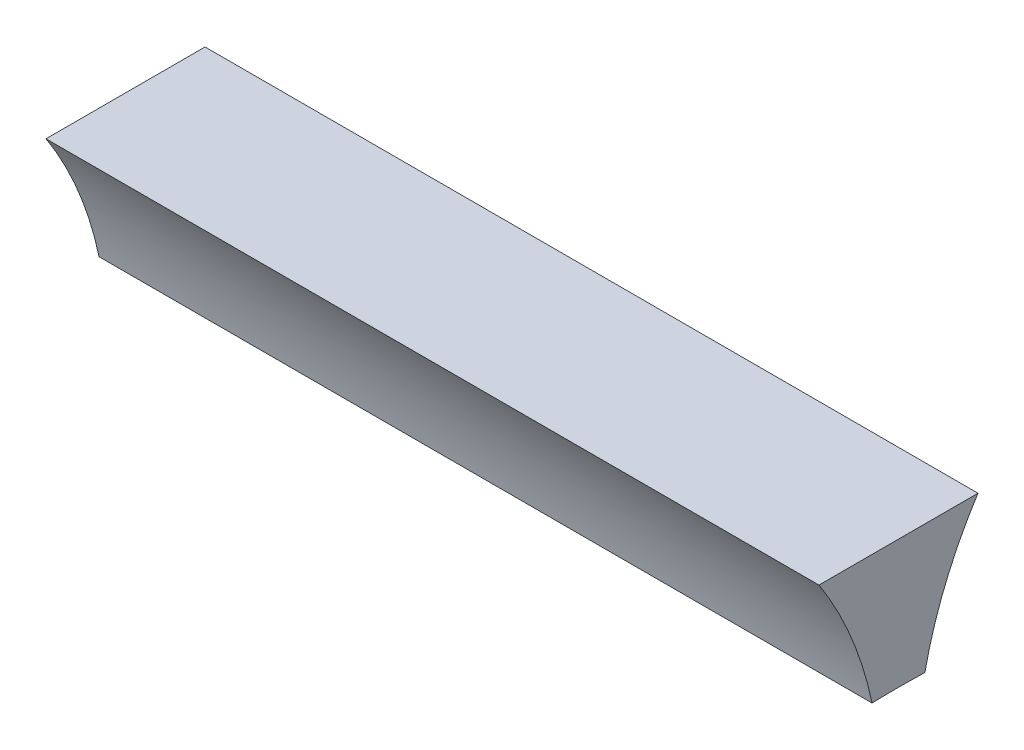
SolidWorks part; units mm, degrees
ref_plane "Plane1" through (0, 0, 0) normal (0, 0, 1) x (1, 0, 0)
ref_plane "Plane2" through (0, 0, 0) normal (0, 1, 0) x (1, 0, 0)
ref_plane "Plane3" through (0, 0, 0) normal (1, 0, 0) x (0, 0, -1)
sketch "HoldingSke" plane through (0, 0, 0) normal (0, 1, 0) x (1, 0, 0)
  line L0 (0, 0) -> (0.5591, -0.3631)
  line L1 (-15, 0) -> (100, 0) construction
  line L2 (0, 0) -> (-2.1039, 2.3779)
  line L3 (0, 0) -> (-11.863, 4.5341)
  line L4 (0, 0) -> (7.2428, 4.7035)
  line L5 (0, 0) -> (-46.8476, -17.4728)
  line L6 (0, 0) -> (-16.5793, -11.1861)
  line L7 (-2.1039, 2.3779) -> (8.6586, 51.2059)
  line L8 (-76.2, 54.61) -> (-72.9, 54.61)
  line L9 (-71.009, 38.7566) -> (-53.1078, 45.2721)
  line L10 (-76.2, 71.12) -> (104.1128, 71.12)
  line L11 (0, 0) -> (-20, 0)
  line L12 (-76.2, 101.6) -> (-76.147, 101.6)
  line L13 (24.9733, 27.94) -> (52.9518, 28.4284)
  line L14 (24.9733, 27.94) -> (24.9743, 27.94)
  line L15 (24.9733, 27.94) -> (100.4006, 29.5858)
  line L16 (-63.627, -1.5) -> (-12.827, -1.5)
  circle A0 centre (0, 0) radius 15
  circle A1 centre (0, 0) radius 22.874
  circle A2 centre (0, 0) radius 37.5
  circle A3 centre (0, 0) radius 15
  dimension "MHD" = 45.748
  dimension "Hub_dia" = 75
  dimension "Bore" = 30
  dimension "MBD" = 30
  dimension "Num_teeth" = 33
  dimension "Pitch" = 0.6667
  dimension "Overall_len" = 50
  dimension "Show_teeth" = 33
  dimension "Thickness" = 20
  dimension "OAL" = 50.0001
  dimension "T_dim" = 3.3
  dimension "Ap" = 20
  dimension "H" = 19.05
  dimension "Pitch_radius" = 180.3128
  dimension "Width" = 20
  dimension "Backlash" = 0.053
  dimension "Addendum_fac" = 1
  dimension "Dedendum_fac" = 1.25
  dimension "Clearance_fac" = 0.25
  dimension "Dedendum_add" = 0.001
  dimension "Module" = 1.5
sketch "BasProSke" plane through (0, 0, 0) normal (0, 1, 0) x (1, 0, 0)
  line L0 (-10, 0) -> (60, 0) construction
  line L1 (0, 0) -> (0, 26.25)
  line L2 (0, 0) -> (20, 0)
  line L3 (20, 0) -> (20, 26.25)
  line L4 (20, 26.25) -> (0, 26.25)
  dimension "Thickness" = 20
  dimension "Diameter" = 52.5
revolve "Base-Revolve" add sketch "BasProSke" angle 360 about L0
sketch "TooCutSke" plane through (0, 0, 0) normal (1, 0, 0) x (0, 0, -1)
  line L1 (0, 0) -> (0, 107) construction
  line L2 (0, 0) -> (-1.2704, 24.7174) construction
  line L3 (0, 0) -> (-4.7008, 49.2285) construction
  line L4 (-1.2704, 24.7174) -> (-2.3504, 24.6142) construction
  arc A0 (0.6837, 22.8638) -> (-0.6837, 22.8638) centre (0, 0) ccw
  arc A1 (2.0575, 26.1947) -> (-2.0575, 26.1947) centre (0, 0) ccw
  circle A2 centre (0, 0) radius 24.75 construction
  circle A3 centre (0, 0) radius 23.2574 construction
  arc A4 (-0.6837, 22.8638) -> (-2.0575, 26.1947) centre (-10.3699, 20.8176) ccw
  arc A5 (2.0575, 26.1947) -> (0.6837, 22.8638) centre (10.3699, 20.8176) ccw
  dimension "Root_dia" = 45.748
  dimension "Overcut_dia" = 52.5508
  dimension "Pitch_dia" = 49.5
  dimension "Base_dia" = 46.5148
  dimension "Flank_rad" = 9.9
  dimension "Half_ang" = 5.455
  dimension "Half_CT" = 1.0849
extrude "ToothCut" cut sketch "TooCutSke" along normal through all
fillet "Breaks" [suppressed] radius 0.03
fillet "RootFillets" [suppressed] radius 0.376
pattern_circular "TeethCuts" count 33 every 10.909 about axis through (-10, 0, 0) along (1, 0, 0) of "ToothCut", "RootFillets", "Breaks"
sketch "HubNeaOneSke" plane through (0, 0, 0) normal (-1, 0, 0) x (0, 0, 1)
  circle A0 centre (0, 0) radius 22.874
  dimension "Diameter" = 45.748
extrude "HubNearOne" [suppressed] add sketch "HubNeaOneSke" along normal blind 30.0001
sketch "HubNeaBotSke" plane through (0, 0, 0) normal (-1, 0, 0) x (0, 0, 1)
  circle A0 centre (0, 0) radius 22.874
  dimension "Diameter" = 45.748
extrude "HubNearBoth" [suppressed] add sketch "HubNeaBotSke" along normal blind 15
ref_plane "FarPln" through (20, 0, 0) normal (1, 0, 0) x (0, 0, -1)
sketch "HubFarSke" plane through (20, 0, 0) normal (1, 0, 0) x (0, 0, -1)
  circle A0 centre (0, 0) radius 22.874
  dimension "Diameter" = 45.748
extrude "HubFar" [suppressed] add sketch "HubFarSke" along normal blind 15
sketch "BorSke" plane through (0, 0, 0) normal (1, 0, 0) x (0, 0, -1)
  circle A0 centre (0, 0) radius 15
  dimension "Diameter" = 30
extrude "Bore" cut sketch "BorSke" along normal mid plane 100.0001
sketch "KeySke" plane through (0, 0, 0) normal (1, 0, 0) x (0, 0, -1)
  line L0 (-5, 0) -> (-5, 18.3)
  line L1 (-5, 18.3) -> (5, 18.3)
  line L2 (5, 18.3) -> (5, 0)
  line L3 (0, 0) -> (0, 34) construction
  line L4 (-5, 0) -> (5, 0)
  dimension "Offset" = 18.3
  dimension "Width" = 10
extrude "Keyway" cut sketch "KeySke" along normal mid plane 100.0001
pattern_circular "Keyway2" [suppressed] count 2 every 90 about axis through (-10, 0, 0) along (1, 0, 0)
sketch "Эскиз1" plane through (20, 0, 0) normal (1, 0, 0) x (0, 0, -1)
  line L0 (5, 18.3) -> (-5, 18.3) construction
  line L2 (5, 14.1421) -> (5, 18.3) construction
  line L3 (-5, 18.3) -> (-5, 14.1421) construction
  line L4 (5, 18.3) -> (-5, 18.3)
  line L5 (5, 14.1421) -> (5, 18.3)
  line L6 (-5, 18.3) -> (-5, 14.1421)
  circle A2 centre (0, 0) radius 28
  arc A4 (-5, 14.1421) -> (5, 14.1421) centre (0, 0) ccw construction
  arc A5 (-5, 14.1421) -> (5, 14.1421) centre (0, 0) ccw
  dimension "D1" = 56
extrude "Бобышка-Вытянуть2" add sketch "Эскиз1" along normal blind 1 contours A2
sketch "Эскиз2" plane through (0, 0, 0) normal (-1, 0, 0) x (0, 0, 1)
  line L0 (-5, 18.3) -> (-5, 14.1421) construction
  line L1 (5, 18.3) -> (-5, 18.3) construction
  line L2 (5, 14.1421) -> (5, 18.3) construction
  line L3 (-5, 18.3) -> (-5, 14.1421)
  line L4 (5, 18.3) -> (-5, 18.3)
  line L5 (5, 14.1421) -> (5, 18.3)
  arc A0 (-5, 14.1421) -> (5, 14.1421) centre (0, 0) ccw construction
  circle A1 centre (0, 0) radius 28 construction
  arc A2 (-5, 14.1421) -> (5, 14.1421) centre (0, 0) ccw
  circle A3 centre (0, 0) radius 28
extrude "Бобышка-Вытянуть3" add sketch "Эскиз2" along normal blind 1
ref_plane "Плоскость1" through (10, 0, 0) normal (1, 0, 0) x (0, 0, -1)
sketch "Эскиз4" plane through (10, 0, 0) normal (1, 0, 0) x (0, 0, -1)
  line L0 (-2.0575, 26.1947) -> (2.0575, 26.1947)
  arc A4 (0.6837, 22.8638) -> (-0.6837, 22.8638) centre (0, 0) ccw
  arc A5 (-0.6837, 22.8638) -> (-2.0575, 26.1947) centre (-10.3699, 20.8176) ccw
  arc A6 (2.0575, 26.1947) -> (-2.0575, 26.1947) centre (0, 0) ccw
  arc A7 (2.0575, 26.1947) -> (0.6837, 22.8638) centre (10.3699, 20.8176) ccw
  arc A8 (0.6837, 22.8638) -> (-0.6837, 22.8638) centre (0, 0) ccw
  arc A9 (-0.6837, 22.8638) -> (-2.0575, 26.1947) centre (-10.3699, 20.8176) ccw
  arc A11 (2.0575, 26.1947) -> (0.6837, 22.8638) centre (10.3699, 20.8176) ccw
  dimension "D1" = 0
extrude "Бобышка-Вытянуть4" add sketch "Эскиз4" along normal mid plane 20 separate body
delete or keep bodies "Тело-Удалить/Сохранить 1" type delete bodies bodies 107
ref_plane "Плоскость2" through (10, 0, 0) normal (1, 0, 0) x (0, 0, -1)
sketch "Эскиз5" plane through (10, 0, 0) normal (1, 0, 0) x (0, 0, -1)
  arc A0 (2.0575, 26.1947) -> (0.6837, 22.8638) centre (10.3699, 20.8176) ccw construction
  arc A1 (2.0575, 26.1947) -> (0.6837, 22.8638) centre (10.3699, 20.8176) ccw
  point P4 (2.0575, 26.1947)
equation "' \"Module@HoldingSke\" = 6.35"
equation "' \"Num_teeth@HoldingSke\" = 12"
equation "' \"Ap@HoldingSke\" =  20"
equation "' \"Ap@HoldingSke\" = 20"
equation "' \"Width@HoldingSke\" = 0.5 * 25.4"
equation "' \"Hub_dia@HoldingSke\"= 1 * 25.4"
equation "' \"Hub_dia@HoldingSke\" = 1 * 25.4"
equation "' \"Overall_len@HoldingSke\" = 1.0 * 25.4"
equation "' \"Bore@HoldingSke\" = 0.75 * 25.4"
equation "' \"T_dim@HoldingSke\" = 0.1 * 25.4"
equation "' \"Width@KeySke\" = 0.25 * 25.4"
equation "' \"Show_teeth@HoldingSke\" = 13"
equation "' \"Backlash@HoldingSke\" = 0.009 * 25.4"
equation "' \"Addendum_fac@HoldingSke\" = 1.0"
equation "' \"Dedendum_fac@HoldingSke\" = 1.25"
equation "' \"Dedendum_add@HoldingSke\" = 0.00005 * 25.4"
equation "' \"Clearance_fac@HoldingSke\" = 0.25"
equation "\"Pitch@HoldingSke\" = 1 / \"Module@HoldingSke\""
equation "\"Overcut_dia@TooCutSke\" = (\"Num_teeth@HoldingSke\" + 2 * \"Addendum_fac@HoldingSke\") / \"Pitch@HoldingSke\" + 0.002 * 25.4"
equation "\"Pitch_dia@TooCutSke\" = \"Num_teeth@HoldingSke\" / \"Pitch@HoldingSke\""
equation "\"Base_dia@TooCutSke\" = \"Num_teeth@HoldingSke\" / \"Pitch@HoldingSke\" * cos((\"Ap@HoldingSke\"  * 3.14159265 / 180))"
equation "\"Root_dia@TooCutSke\" = (\"Num_teeth@HoldingSke\" + 2) / \"Pitch@HoldingSke\" - 2 * (\"Addendum_fac@HoldingSke\" + \"Dedendum_fac@HoldingSke\") / \"Pitch@HoldingSke\" - \"Dedendum_add@HoldingSke\" * 2"
equation "\"Half_ang@TooCutSke\" = 180 / \"Num_teeth@HoldingSke\""
equation "\"Half_CT@TooCutSke\" = \"Num_teeth@HoldingSke\" / \"Pitch@HoldingSke\" * sin((3.14159265 / 2 / \"Num_teeth@HoldingSke\")) / 2 - 7 * \"Backlash@HoldingSke\" / 4"
equation "\"Flank_rad@TooCutSke\" = \"Num_teeth@HoldingSke\" / \"Pitch@HoldingSke\" / 5"
equation "\"Radius@RootFillets\" = \"Clearance_fac@HoldingSke\" / \"Pitch@HoldingSke\" + \"Dedendum_add@HoldingSke\""
equation "\"Break_rad@Breaks\" = 0.02 / \"Pitch@HoldingSke\""
equation "\"Thickness@HoldingSke\" = \"Width@HoldingSke\""
equation "\"OAL@HoldingSke\" = \"Thickness@HoldingSke\""
equation "\"MHD@HoldingSke\" = (\"Num_teeth@HoldingSke\" + 2) / \"Pitch@HoldingSke\" - 2 * (\"Addendum_fac@HoldingSke\" + \"Dedendum_fac@HoldingSke\")  / \"Pitch@HoldingSke\" - \"Dedendum_add@HoldingSke\" * 2"
equation "\"MBD@HoldingSke\" = (\"Num_teeth@HoldingSke\" + 2) / \"Pitch@HoldingSke\" - 2 * (\"Addendum_fac@HoldingSke\" + \"Dedendum_fac@HoldingSke\")  / \"Pitch@HoldingSke\" - \"Dedendum_add@HoldingSke\" * 2 - 0.002 * 25.4"
equation "\"MHD@HoldingSke\" = ((sgn( \"MHD@HoldingSke\" - \"Hub_dia@HoldingSke\" )-1)*( \"MHD@HoldingSke\" - \"Hub_dia@HoldingSke\" ))/-2+ \"Hub_dia@HoldingSke\""
equation "\"MBD@HoldingSke\" = ((sgn( \"MBD@HoldingSke\" - \"Bore@HoldingSke\" )-1)*( \"MBD@HoldingSke\" - \"Bore@HoldingSke\" ))/-2+ \"Bore@HoldingSke\""
equation "\"OAL@HoldingSke\" = ((sgn( \"OAL@HoldingSke\" - \"Overall_len@HoldingSke\" )+1)*( \"OAL@HoldingSke\" - \"Overall_len@HoldingSke\" ))/2 + \"Overall_len@HoldingSke\" + 0.000002 * 25.4"
equation "\"Num_teeth@TeethCuts\" = int( \"Show_teeth@HoldingSke\" ) + 1"
equation "\"Num_teeth@TeethCuts\" = ((sgn( \"Num_teeth@TeethCuts\" - \"Num_teeth@HoldingSke\" )-1)*( \"Num_teeth@TeethCuts\" - \"Num_teeth@HoldingSke\" ))/-2+ \"Num_teeth@HoldingSke\""
equation "\"Num_teeth@TeethCuts\" = ((sgn( \"Num_teeth@TeethCuts\" - 2.0)+1)*( \"Num_teeth@TeethCuts\" - 2.0))/2 +2.0"
equation "\"Angle@TeethCuts\" = 360.0 / \"Num_teeth@HoldingSke\""
equation "\"Diameter@BasProSke\" = (\"Num_teeth@HoldingSke\" + 2 * \"Addendum_fac@HoldingSke\") / \"Pitch@HoldingSke\""
equation "\"Thickness@BasProSke\"  = \"Thickness@HoldingSke\""
equation "' \"Fillet_rad@BasProSke\" =  \"Thickness@HoldingSke\" * 0.05"
equation "' \"Fillet_rad@BasProSke\" = \"Thickness@HoldingSke\" * 0.05"
equation "\"MHD@HoldingSke\" = ((sgn( \"MHD@HoldingSke\" - \"Root_dia@TooCutSke\" )-1)*( \"MHD@HoldingSke\" - \"Root_dia@TooCutSke\" ))/-2+ \"Root_dia@TooCutSke\""
equation "\"Diameter@HubNeaOneSke\" = \"MHD@HoldingSke\""
equation "\"Length@HubNearOne\" = \"OAL@HoldingSke\" - \"Thickness@BasProSke\""
equation "\"Diameter@HubNeaBotSke\" = \"MHD@HoldingSke\""
equation "\"Length@HubNearBoth\" = ( \"OAL@HoldingSke\" - \"Thickness@BasProSke\" ) / 2.0"
equation "\"Thickness@FarPln\" = \"Thickness@BasProSke\""
equation "\"Diameter@HubFarSke\" = \"MHD@HoldingSke\""
equation "\"Length@HubFar\" = ( \"OAL@HoldingSke\" - \"Thickness@BasProSke\" ) / 2.0"
equation "\"Diameter@BorSke\" = \"MBD@HoldingSke\""
equation "\"D1@Bore\" = \"OAL@HoldingSke\" * 2.0"
equation "\"D1@Keyway\" = \"OAL@HoldingSke\" * 2.0"
equation "\"Offset@KeySke\" = \"T_dim@HoldingSke\" + \"MBD@HoldingSke\" / 2.0"
